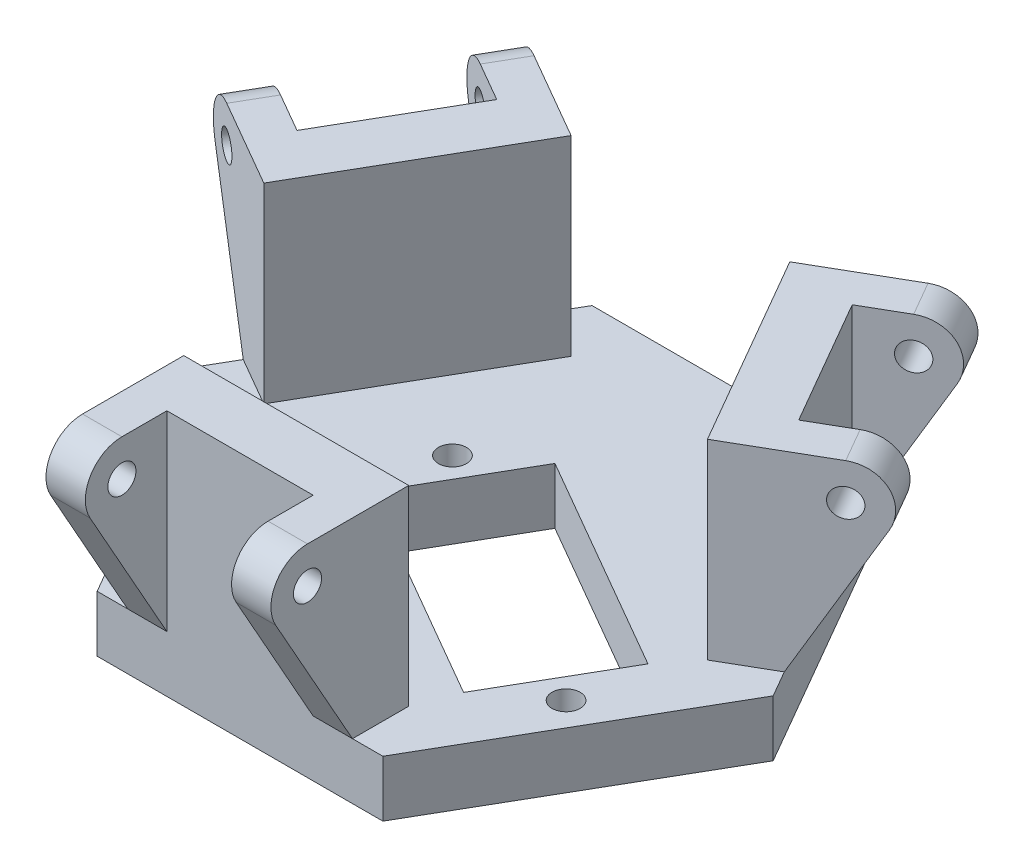
SolidWorks part; units mm, degrees
ref_plane "Front Plane" through (0, 0, 0) normal (0, 0, 1) x (1, 0, 0)
ref_plane "Top Plane" through (0, 0, 0) normal (0, 1, 0) x (1, 0, 0)
ref_plane "Right Plane" through (0, 0, 0) normal (1, 0, 0) x (0, 0, -1)
sketch "Sketch1" plane through (0, 0, 0) normal (0, 1, 0) x (1, 0, 0)
  line L0 (25.4034, 0) -> (12.7017, 22)
  line L1 (12.7017, 22) -> (-12.7017, 22)
  line L2 (-12.7017, 22) -> (-25.4034, 0)
  line L3 (-25.4034, 0) -> (-12.7017, -22)
  line L4 (-12.7017, -22) -> (12.7017, -22)
  line L5 (12.7017, -22) -> (25.4034, 0)
  circle A0 centre (0, 0) radius 25.4034 construction
  dimension "D1" = 22
extrude "Boss-Extrude1" add sketch "Sketch1" along normal blind 5
sketch "Sketch4" plane through (0, 5, 0) normal (0, 1, 0) x (1, 0, 0)
  line L0 (-12.7017, -22) -> (12.7017, -22) construction
  line L1 (-10, -22) -> (10, -22)
  line L2 (-10, -22) -> (-10, -17)
  line L3 (-10, -17) -> (10, -17)
  line L4 (10, -22) -> (10, -17)
  point P6 (0, -22)
  point P7 (0, -22)
  dimension "D1" = 20
  dimension "D2" = 5
extrude "Boss-Extrude3" add sketch "Sketch4" along normal blind 17
sketch "Sketch2" plane through (0, 0, 0) normal (1, 0, 0) x (0, 0, -1)
  line L0 (-22, 22) -> (-26, 22)
  line L1 (-22, 5) -> (-22, 0) construction
  line L3 (-22, 22) -> (-22, 5)
  line L4 (-22, 5) -> (0, 5) construction
  line L5 (-22, 5) -> (-28.8332, 17.1576)
  arc A0 (-26, 22) -> (-28.8332, 17.1576) centre (-26, 18.75) ccw
  circle A1 centre (-26, 18.75) radius 1.25
  dimension "D1" = 2.5
  dimension "D2" = 4
  dimension "D4" = 17
  dimension "D3" = 2
extrude "Boss-Extrude2" add sketch "Sketch2" along normal up to surface (3.5 mm away) from offset 6.5 up to face at (10, 13.5, 19.5)
mirror "Mirror1" about plane through (0, 0, 0) normal (1, 0, 0) of "Boss-Extrude3", "Boss-Extrude2"
sketch "Sketch5" plane through (0, 0, 0) normal (0, 0, 1) x (1, 0, 0)
  line L0 (0, 0) -> (0, 15.7855) construction
pattern_circular "CirPattern1" count 3 over 360 about axis through (0, 0, 0) along (0, 1, 0) of "Mirror1", "Boss-Extrude3", "Boss-Extrude2"
sketch "Sketch3" plane through (0, 5, 0) normal (0, 1, 0) x (1, 0, 0)
  line L0 (-5.1962, 3) -> (0, 0) construction
  line L1 (-2.1962, 8.1962) -> (17.376, -3.1038)
  line L2 (-2.1962, 8.1962) -> (-8.1962, -2.1962)
  line L3 (-8.1962, -2.1962) -> (11.376, -13.4962)
  line L4 (17.376, -3.1038) -> (11.376, -13.4962)
  line L5 (12.7017, -22) -> (25.4034, 0) construction
  point P7 (-5.1962, 3)
  dimension "D1" = 22.6
  dimension "D2" = 12
  dimension "D3" = 6
extrude "Cut-Extrude1" cut sketch "Sketch3" against normal up to next
sketch "Sketch6" plane through (0, 5, 0) normal (0, 1, 0) x (1, 0, 0)
  line L0 (-2.1962, 8.1962) -> (-8.1962, -2.1962) construction
  line L1 (11.376, -13.4962) -> (17.376, -3.1038) construction
  line L2 (-7.3612, 4.25) -> (16.5411, -9.55) construction
  circle A0 centre (-7.3612, 4.25) radius 1.25
  circle A1 centre (16.5411, -9.55) radius 1.25
  point P8 (14.376, -8.3)
  point P9 (-5.1962, 3)
  point P10 (-7.3612, 4.25)
  dimension "D3" = 2.5
  dimension "D1" = 2.5
  dimension "D2" = 2.5
extrude "Cut-Extrude2" cut sketch "Sketch6" against normal up to next
sketch "Sketch7" plane through (0, 22, 0) normal (0, 1, 0) x (1, 0, 0)
  line L0 (0, 0) -> (-27.7128, 16) construction
  line L1 (-19.7224, -0.1603) -> (-9.7224, 17.1603) construction
  circle A0 centre (-27.7128, 16) radius 2.7
  point P6 (-14.7224, 8.5)
  dimension "D2" = 5.4
  dimension "D1" = 32
equation "\"D2@Sketch2\"=\"D1@Sketch2\"+1.5mm"
